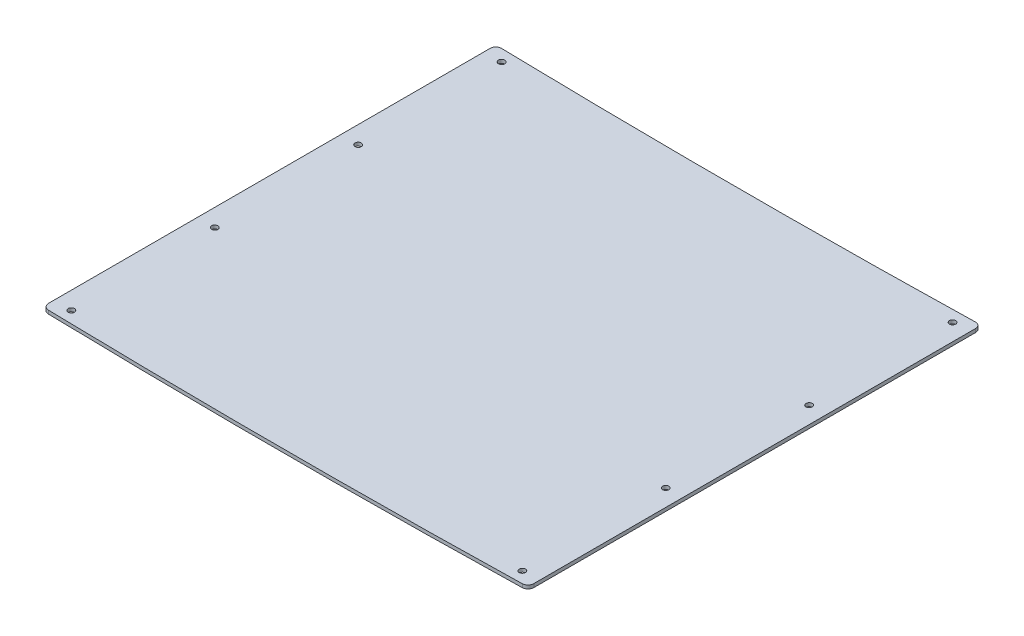
SolidWorks part; units mm, degrees
material "AISI 1020"
ref_plane "Plano frontal" through (0, 0, 0) normal (0, 0, 1) x (1, 0, 0)
ref_plane "Plano superior" through (0, 0, 0) normal (0, 1, 0) x (1, 0, 0)
ref_plane "Plano direito" through (0, 0, 0) normal (1, 0, 0) x (0, 0, -1)
sketch "Esboço1" plane through (0, 0, 0) normal (0, 0, 1) x (1, 0, 0)
  line L0 (0, 0) -> (423, 0) construction
  arc A0 (0, 0) -> (423, 0) centre (211.5, 8945.2) ccw
  dimension "D1" = 423
  dimension "D2" = 5
extrude "Extrusão-Fina1" add sketch "Esboço1" along normal mid plane 395 thin
fillet "Filete1" radius 5 4 edges at (-0.0355, -1.4996, 197.5) (-0.0355, -1.4996, -197.5) (423.0355, -1.4996, -197.5) (423.0355, -1.4996, 197.5)
sketch "Esboço2" plane through (0, 0, 0) normal (0, 1, 0) x (1, 0, 0)
  line L0 (-0.0709, -192.5) -> (-0.0709, 192.5) construction
  line L1 (4.9277, -197.5) -> (418.0723, -197.5) construction
  line L2 (423, -192.5) -> (423, 192.5) construction
  line L3 (4.9986, -197.5) -> (418.0014, -197.5) construction
  circle A0 centre (14.9291, -187.5) radius 2.75
  circle A1 centre (408, -187.5) radius 2.75
  dimension "D1" = 15
  dimension "D2" = 10
  dimension "D3" = 5.5
  dimension "D4" = 15
  dimension "D5" = 5.5
  dimension "D6" = 10
extrude "Corte-extrusão1" cut sketch "Esboço2" against normal through all
sketch "Esboço3" plane through (0, 0, 0) normal (0, 1, 0) x (1, 0, 0)
  line L0 (211.5, -197.5) -> (211.5, 197.5) construction
  line L1 (4.9986, -197.5) -> (418.0014, -197.5) construction
  line L2 (418.0014, 197.5) -> (4.9986, 197.5) construction
pattern_linear "Padrão linear2" count 4 spacing 125 along (0, 0, -1) of "Corte-extrusão1"
